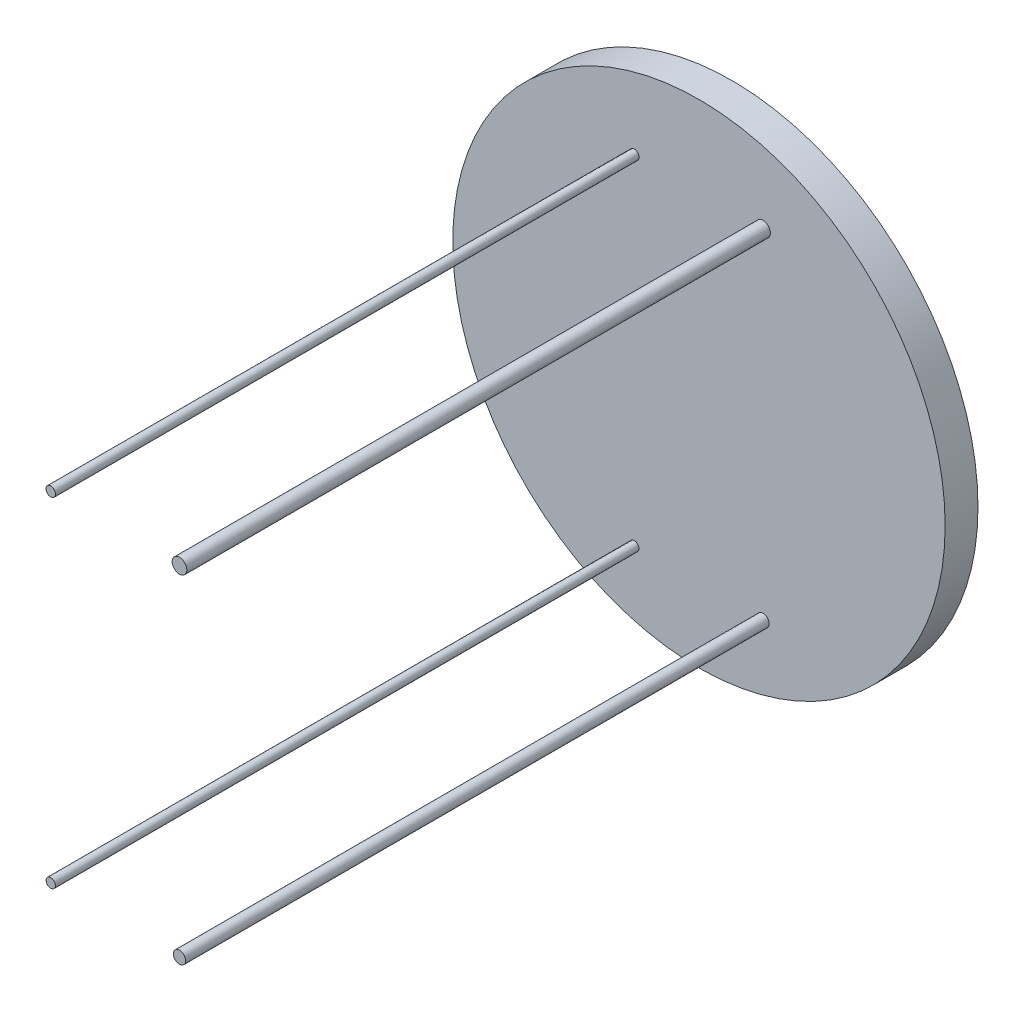
SolidWorks part; units mm, degrees
ref_plane "Front Plane" through (0, 0, 0) normal (0, 0, 1) x (1, 0, 0)
ref_plane "Top Plane" through (0, 0, 0) normal (0, 1, 0) x (1, 0, 0)
ref_plane "Right Plane" through (0, 0, 0) normal (1, 0, 0) x (0, 0, -1)
sketch "Sketch1" plane through (0, 0, 943.5108) normal (0, 0, 1) x (1, 0, 0)
  circle A0 centre (833.9306, -1197.1664) radius 1304.0928
extrude "Boss-Extrude1" add sketch "Sketch1" against normal blind 174
sketch "Sketch3" plane through (0, 0, 943.5108) normal (0, 0, 1) x (1, 0, 0)
  circle A0 centre (1173.6392, -317.2016) radius 38.7717
  circle A1 centre (491.7651, -317.2016) radius 25.193
  circle A2 centre (491.7651, -2112.8608) radius 24.5211
  circle A3 centre (1173.6392, -2112.8608) radius 32.2545
extrude "Boss-Extrude2" add sketch "Sketch3" along normal blind 3091
